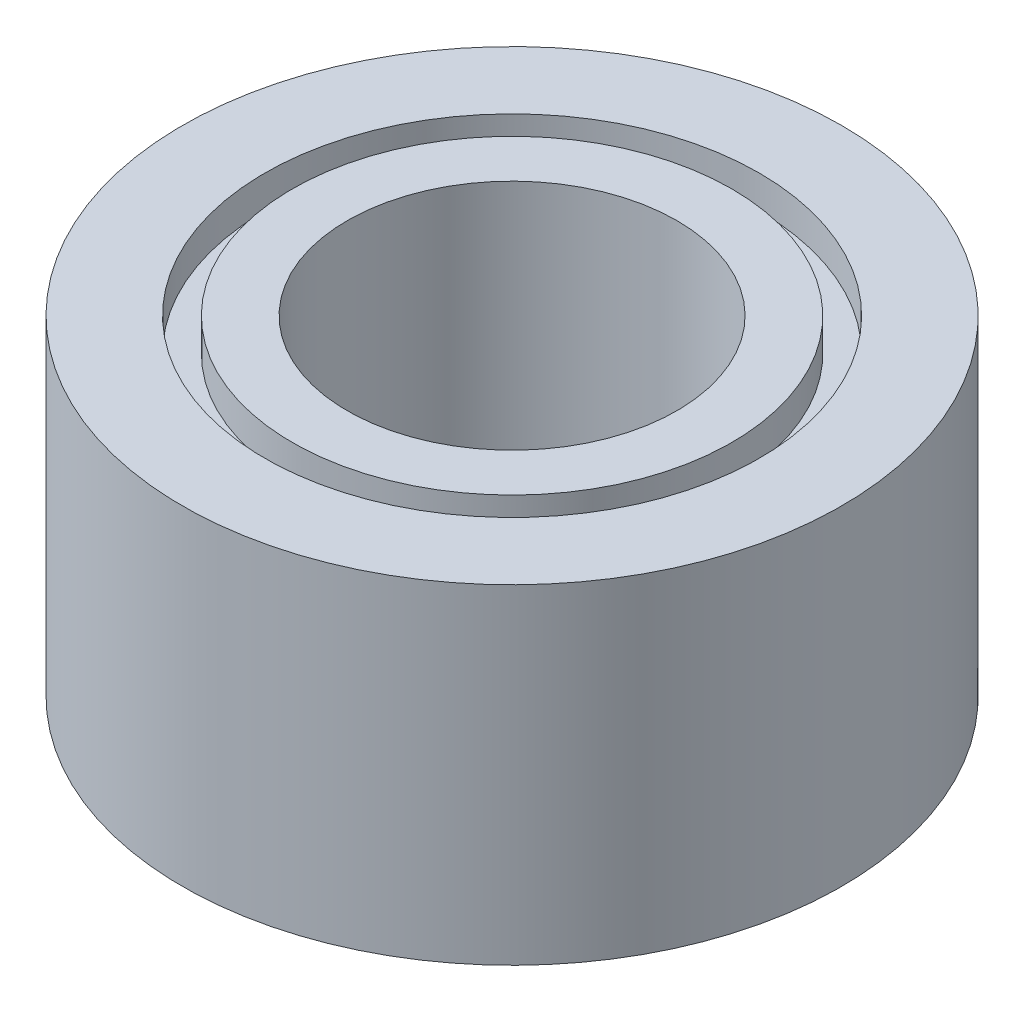
SolidWorks part; units mm, degrees
material "镀铬不锈钢"
ref_plane "前视基准面" through (0, 0, 0) normal (0, 0, 1) x (1, 0, 0)
ref_plane "上视基准面" through (0, 0, 0) normal (0, 1, 0) x (1, 0, 0)
ref_plane "右视基准面" through (0, 0, 0) normal (1, 0, 0) x (0, 0, -1)
sketch "草图1" plane through (0, 0, 0) normal (1, 0, 0) x (0, 0, -1)
  line L0 (0, 0) -> (-1.5, 0) construction
  line L1 (-1.5, 1.5) -> (-1.5, -1.5)
  line L2 (-1.5, 1.5) -> (-2, 1.5)
  line L3 (-2, 1.5) -> (-2, 1.2)
  line L4 (-2, 1.2) -> (-2.25, 1.2)
  line L5 (-2.25, 1.2) -> (-2.25, 1.5)
  line L6 (-2.25, 1.5) -> (-3, 1.5)
  line L7 (-3, 1.5) -> (-3, -1.5)
  line L8 (-1.5, 0) -> (-3, 0) construction
  line L9 (-2.25, -1.5) -> (-3, -1.5)
  line L10 (-2.25, -1.2) -> (-2.25, -1.5)
  line L11 (-2, -1.2) -> (-2.25, -1.2)
  line L12 (-2, -1.5) -> (-2, -1.2)
  line L13 (-1.5, -1.5) -> (-2, -1.5)
  line L14 (0, 0) -> (0, 1.5)
  point P7 (-1.5, 0)
  dimension "D1" = 1.5
  dimension "D2" = 1.5
  dimension "D3" = 0.75
  dimension "D4" = 0.5
  dimension "D5" = 0.3
  dimension "D6" = 1.5
revolve "旋转1" add sketch "草图1" angle 360 about L14
